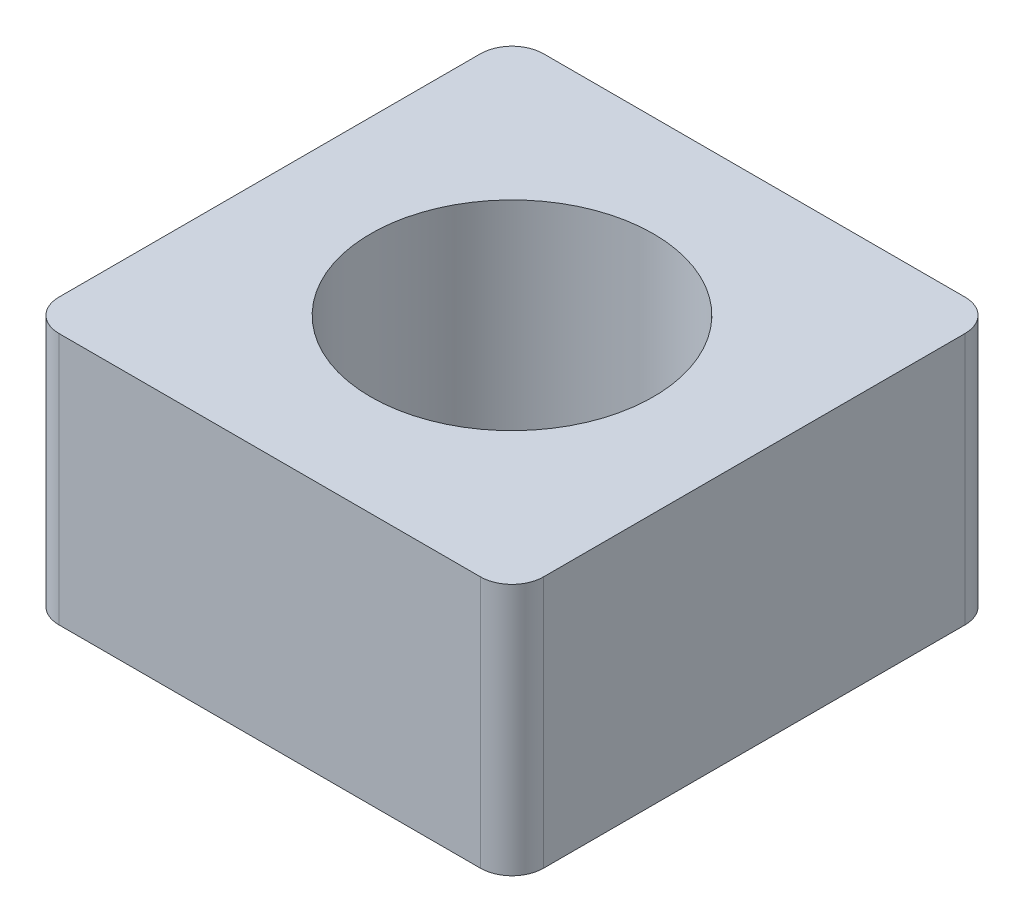
SolidWorks part; units mm, degrees
ref_plane "Front Plane" through (0, 0, 0) normal (0, 0, 1) x (1, 0, 0)
ref_plane "Top Plane" through (0, 0, 0) normal (0, 1, 0) x (1, 0, 0)
ref_plane "Right Plane" through (0, 0, 0) normal (1, 0, 0) x (0, 0, -1)
sketch "Sketch1" plane through (0, 0, 0) normal (0, 1, 0) x (1, 0, 0)
  line L1 (-3.048, -3.048) -> (3.048, -3.048)
  line L2 (-3.048, -3.048) -> (-3.048, 3.048)
  line L3 (-3.048, 3.048) -> (3.048, 3.048)
  line L4 (3.048, -3.048) -> (3.048, 3.048)
  line L5 (-3.048, -3.048) -> (3.048, 3.048) construction
  line L6 (-3.048, 3.048) -> (3.048, -3.048) construction
  circle A0 centre (0, 0) radius 1.778
  point P0 (0, 0)
  dimension "D2" = 3.556
  dimension "D1" = 6.096
extrude "Boss-Extrude1" add sketch "Sketch1" along normal blind 3.175
fillet "Fillet1" radius 0.3969 4 edges at (-3.048, 1.5875, 3.048) (3.048, 1.5875, 3.048) (3.048, 1.5875, -3.048) (-3.048, 1.5875, -3.048)
